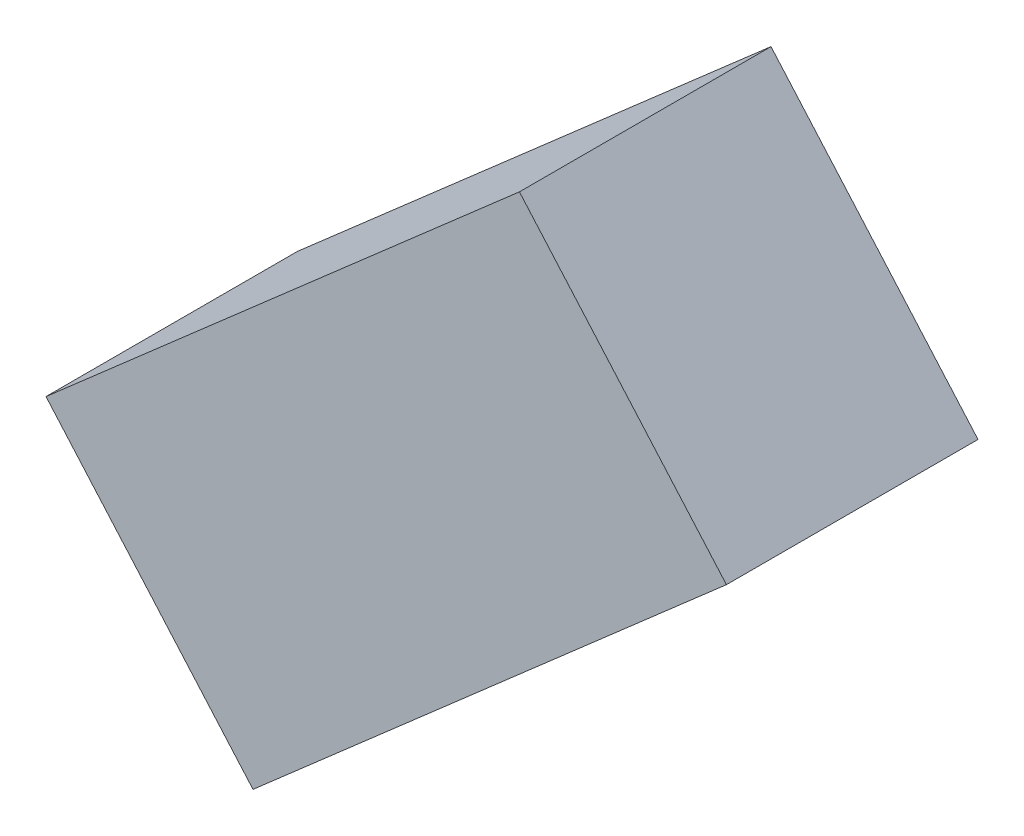
SolidWorks part; units mm, degrees
ref_plane "前视基准面" through (0, 0, 0) normal (0, 0, 1) x (1, 0, 0)
ref_plane "上视基准面" through (0, 0, 0) normal (0, 1, 0) x (1, 0, 0)
ref_plane "右视基准面" through (0, 0, 0) normal (1, 0, 0) x (0, 0, -1)
other "Configuration Table"
sketch "草图1" plane through (0, 0, 0) normal (0, 0, 1) x (1, 0, 0)
  line L8 (-49.7922, 68.9141) -> (-64.848, 55.7488)
  line L9 (-64.848, 55.7488) -> (-58.2654, 48.2209)
  line L10 (-58.2654, 48.2209) -> (-43.2096, 61.3862)
  line L11 (-43.2096, 61.3862) -> (-49.7922, 68.9141)
  dimension "D1" = 20
  dimension "D2" = 10
extrude "凸台-拉伸1" add sketch "草图1" along normal blind 8
